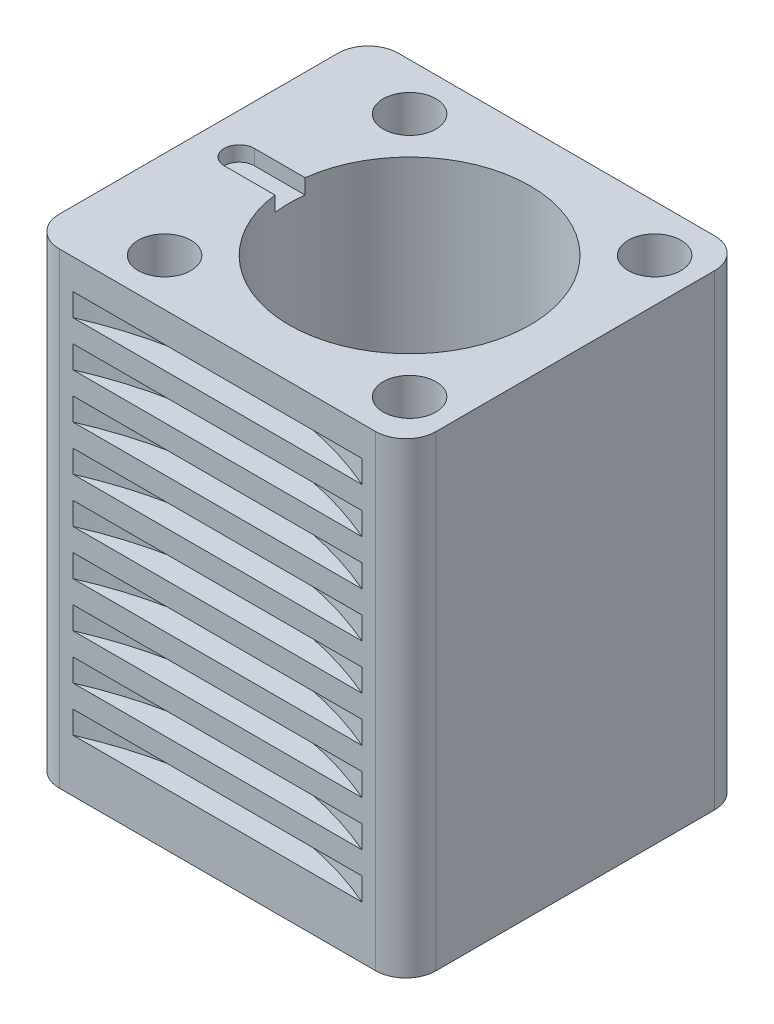
SolidWorks part; units mm, degrees
ref_plane "Front Plane" through (0, 0, 0) normal (0, 0, 1) x (1, 0, 0)
ref_plane "Top Plane" through (0, 0, 0) normal (0, 1, 0) x (1, 0, 0)
ref_plane "Right Plane" through (0, 0, 0) normal (1, 0, 0) x (0, 0, -1)
sketch "Sketch3" plane through (0, 0, 0) normal (0, 1, 0) x (1, 0, 0)
  line L1 (18, 22.5) -> (-24, 22.5)
  line L2 (22, 18.5) -> (22, -18.5)
  line L3 (18, -22.5) -> (-24, -22.5)
  line L4 (-28, 18.5) -> (-28, -18.5)
  arc A0 (-24, -22.5) -> (-28, -18.5) centre (-24, -18.5) cw
  arc A1 (22, -18.5) -> (18, -22.5) centre (18, -18.5) cw
  arc A2 (18, 22.5) -> (22, 18.5) centre (18, 18.5) cw
  arc A3 (-24, 22.5) -> (-28, 18.5) centre (-24, 18.5) ccw
  point P9 (22, -22.5)
  point P12 (22, 22.5)
  point P15 (-28, 22.5)
  dimension "D5" = 4
  dimension "D1" = 50
  dimension "D2" = 45
  dimension "D3" = 22.5
  dimension "D4" = 22
extrude "Boss-Extrude2" add sketch "Sketch3" along normal blind 62
sketch "Sketch4" plane through (0, 0, 0) normal (0, -1, 0) x (1, 0, 0)
  circle A0 centre (0, 0) radius 18
extrude "Boss-Extrude3" add sketch "Sketch4" along normal blind 2
sketch "Sketch5" plane through (0, -2, 0) normal (0, -1, 0) x (1, 0, 0)
  circle A0 centre (0, 0) radius 16
extrude "Cut-Extrude1" cut sketch "Sketch5" against normal through all
sketch "Sketch6" plane through (0, 62, 0) normal (0, 1, 0) x (1, 0, 0)
  line L1 (-22.61, 2) -> (-13.6435, 2)
  line L3 (-22.61, -2) -> (-13.6435, -2)
  line L4 (-13.6435, 2) -> (-13.6435, -2)
  arc A0 (-22.61, 2) -> (-22.61, -2) centre (-22.61, 0) ccw
  dimension "D1" = 4
  dimension "D2" = 2
extrude "Cut-Extrude2" cut sketch "Sketch6" against normal blind 2
sketch "Sketch7" plane through (0, 62, 0) normal (0, 1, 0) x (1, 0, 0)
  line L0 (0, 0) -> (23, 0) construction
  line L1 (0, 0) -> (16.2635, 16.2635) construction
  circle A0 centre (0, 0) radius 23
  circle A1 centre (16.2635, 16.2635) radius 3.5
  circle A2 centre (16.2635, -16.2635) radius 3.5
  circle A3 centre (-16.2635, -16.2635) radius 3.5
  circle A4 centre (-16.2635, 16.2635) radius 3.5
  point P15 (0, 0)
  dimension "D1" = 45
  dimension "D2" = 4
extrude "Cut-Extrude3" cut sketch "Sketch7" against normal through all contours A4 | A3 | A2 | A1
ref_plane "Plane1" through (-3, 0, 0) normal (1, 0, 0) x (0, 0, -1)
sketch "Sketch8" plane through (-3, 0, 0) normal (1, 0, 0) x (0, 0, -1)
  line L0 (-18.5, 62) -> (-22.5, 62) construction
  line L1 (-18.5, 58) -> (-66.5, 58)
  line L2 (-18.5, 58) -> (-18.5, 55)
  line L3 (-18.5, 55) -> (-66.5, 55)
  line L4 (-66.5, 58) -> (-66.5, 55)
  line L5 (-22.5, 62) -> (-22.5, 0) construction
  dimension "D1" = 4
  dimension "D2" = 3
  dimension "D3" = 4
  dimension "D4" = 48
revolve "Cut-Revolve1" cut sketch "Sketch8" angle 360 about L4
pattern_linear "LPattern1" count 9 spacing 6 along (0, -1, 0) of "Cut-Revolve1"
mirror "Mirror1" about plane through (0, 0, 0) normal (0, 0, 1) of "LPattern1", "Cut-Revolve1"
sketch "Sketch10" plane through (0, 0, 0) normal (0, 0, 1) x (1, 0, 0)
  line L0 (-24, 62) -> (-28, 62) construction
  line L1 (-24, 58) -> (-72, 58)
  line L2 (-24, 58) -> (-24, 55)
  line L3 (-24, 55) -> (-72, 55)
  line L4 (-72, 58) -> (-72, 55)
  line L5 (-28, 62) -> (-28, 0) construction
  point P6 (-26, 62)
  dimension "D1" = 4
  dimension "D2" = 4
  dimension "D3" = 3
  dimension "D4" = 48
revolve "Cut-Revolve3" cut sketch "Sketch10" angle 360 about L4
pattern_linear "LPattern2" count 9 spacing 6 along (0, -1, 0) of "Cut-Revolve3"
